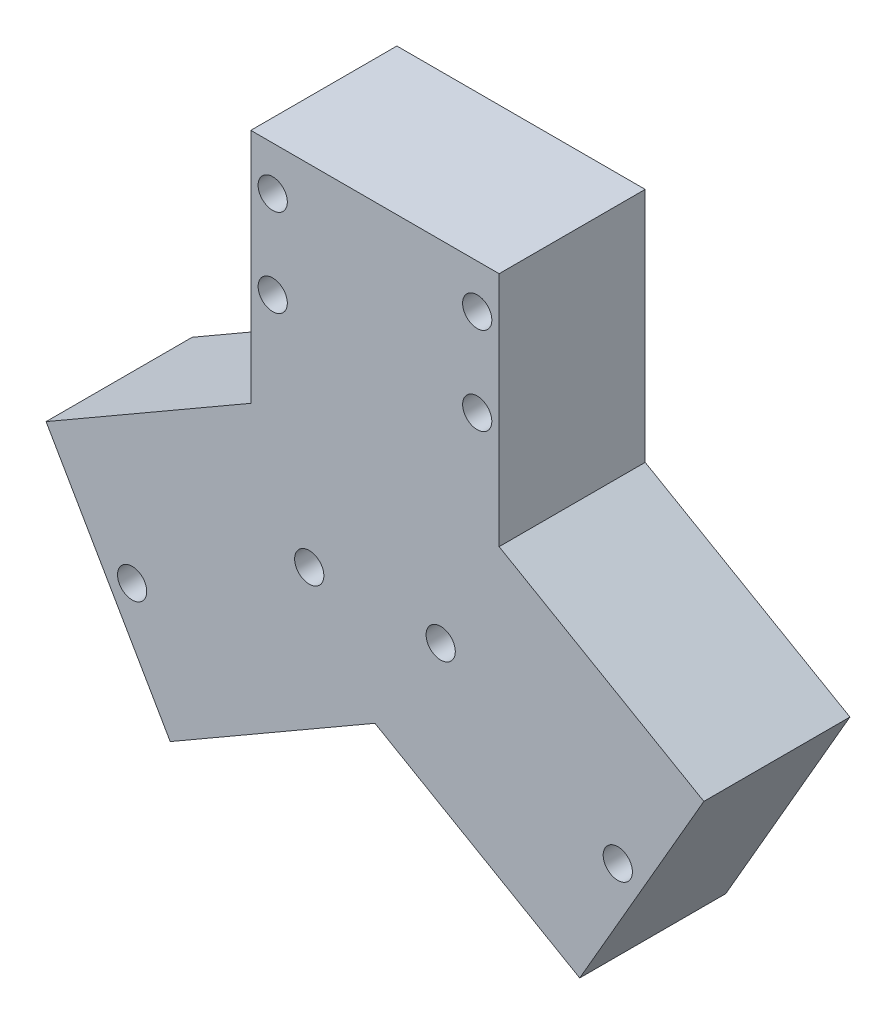
SolidWorks part; units mm, degrees
ref_plane "Front Plane" through (0, 0, 0) normal (0, 0, 1) x (1, 0, 0)
ref_plane "Top Plane" through (0, 0, 0) normal (0, 1, 0) x (1, 0, 0)
ref_plane "Right Plane" through (0, 0, 0) normal (1, 0, 0) x (0, 0, -1)
sketch "Sketch1" plane through (0, 0, 0) normal (0, 0, 1) x (1, 0, 0)
  line L0 (-8.5, 14.7224) -> (-8.5, 30.9075)
  line L1 (-8.5, 30.9075) -> (8.5, 30.9075)
  line L2 (8.5, 30.9075) -> (8.5, 14.7224)
  line L3 (8.5, 14.7224) -> (22.5167, 6.6299)
  line L4 (22.5167, 6.6299) -> (14.0167, -8.0925)
  line L5 (14.0167, -8.0925) -> (0, 0)
  line L6 (0, 0) -> (-14.0167, -8.0925)
  line L7 (-14.0167, -8.0925) -> (-22.5167, 6.6299)
  line L8 (-22.5167, 6.6299) -> (-8.5, 14.7224)
  line L9 (0, 30.9075) -> (0, 27.9075) construction
  line L10 (-7, 27.9075) -> (7, 27.9075) construction
  line L11 (-7, 27.9075) -> (-7, 21.9075) construction
  line L12 (-7, 21.9075) -> (7, 21.9075) construction
  line L13 (7, 27.9075) -> (7, 21.9075) construction
  line L14 (-16.6244, 0) -> (-4.5, 7) construction
  line L15 (16.6244, 0) -> (4.5, 7) construction
  line L16 (-4.5, 7) -> (4.5, 7) construction
  line L17 (0, 7) -> (0, 0) construction
  circle A0 centre (-7, 27.9075) radius 1
  circle A1 centre (7, 27.9075) radius 1
  circle A2 centre (-7, 21.9075) radius 1
  circle A3 centre (7, 21.9075) radius 1
  circle A4 centre (-16.6244, 0) radius 1
  circle A5 centre (-4.5, 7) radius 1
  circle A6 centre (4.5, 7) radius 1
  circle A7 centre (16.6244, 0) radius 1
  dimension "D6" = 2
  dimension "D1" = 17
  dimension "D2" = 39
  dimension "D3" = 6
  dimension "D4" = 14
  dimension "D5" = 9
  dimension "D7" = 14
  dimension "D8" = 7
  dimension "D9" = 9
extrude "Boss-Extrude1" add sketch "Sketch1" along normal blind 10
